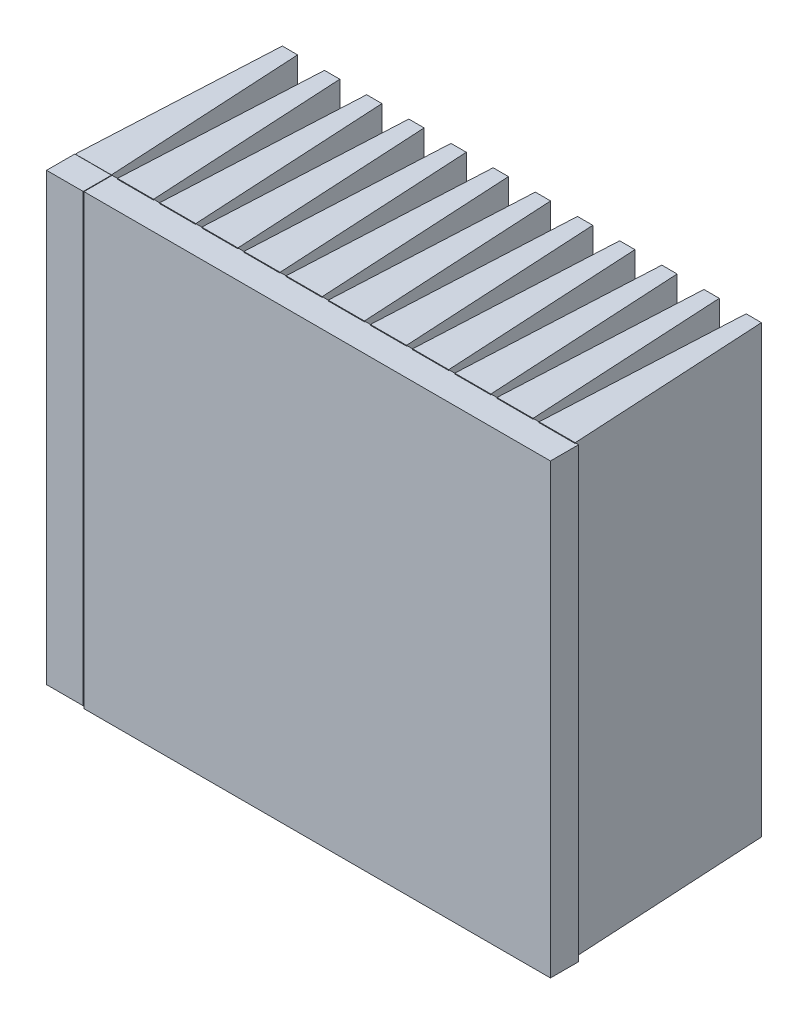
SolidWorks part; units mm, degrees
material "1060 Alloy"
ref_plane "Front Plane" through (0, 0, 0) normal (0, 0, 1) x (1, 0, 0)
ref_plane "Top Plane" through (0, 0, 0) normal (0, 1, 0) x (1, 0, 0)
ref_plane "Right Plane" through (0, 0, 0) normal (1, 0, 0) x (0, 0, -1)
sketch "Sketch1" plane through (0, 0, 0) normal (0, 0, 1) x (1, 0, 0)
  line L0 (-91.5934, 78958.1492) -> (-91.5934, -41.8508)
  line L1 (6408.4066, -41.8508) -> (-91.5934, -41.8508)
  line L2 (6408.4066, -41.8508) -> (6408.4066, 78958.1492)
  line L3 (6408.4066, 78958.1492) -> (-91.5934, 78958.1492)
sketch "Sketch2" plane through (0, 0, 0) normal (0, 1, 0) x (1, 0, 0)
  line L0 (0, 0) -> (1767.7351, 34955.3302)
  line L1 (6408.4066, 0) -> (4484.4459, 34947.0796)
  line L2 (6408.4066, 0) -> (-91.5934, 0) construction
  line L3 (1767.7351, 34955.3302) -> (4484.4459, 34947.0796)
  line L4 (7478.0557, 0) -> (9245.7908, 34955.3302)
  line L5 (13886.4623, 0) -> (11962.5016, 34947.0796)
  line L6 (9245.7908, 34955.3302) -> (11962.5016, 34947.0796)
  line L7 (14956.1114, 0) -> (16723.8465, 34955.3302)
  line L8 (21364.518, 0) -> (19440.5573, 34947.0796)
  line L9 (16723.8465, 34955.3302) -> (19440.5573, 34947.0796)
  line L10 (22434.1671, 0) -> (24201.9022, 34955.3302)
  line L11 (28842.5737, 0) -> (26918.613, 34947.0796)
  line L12 (24201.9022, 34955.3302) -> (26918.613, 34947.0796)
  line L13 (29912.2228, 0) -> (31679.9579, 34955.3302)
  line L14 (36320.6294, 0) -> (34396.6687, 34947.0796)
  line L15 (31679.9579, 34955.3302) -> (34396.6687, 34947.0796)
  line L16 (37390.2785, 0) -> (39158.0136, 34955.3302)
  line L17 (43798.6851, 0) -> (41874.7244, 34947.0796)
  line L18 (39158.0136, 34955.3302) -> (41874.7244, 34947.0796)
  line L19 (44868.3342, 0) -> (46636.0693, 34955.3302)
  line L20 (51276.7408, 0) -> (49352.7801, 34947.0796)
  line L21 (46636.0693, 34955.3302) -> (49352.7801, 34947.0796)
  line L22 (52346.3898, 0) -> (54114.1249, 34955.3302)
  line L23 (58754.7965, 0) -> (56830.8357, 34947.0796)
  line L24 (54114.1249, 34955.3302) -> (56830.8357, 34947.0796)
  line L25 (59824.4455, 0) -> (61592.1806, 34955.3302)
  line L26 (66232.8521, 0) -> (64308.8914, 34947.0796)
  line L27 (61592.1806, 34955.3302) -> (64308.8914, 34947.0796)
  line L28 (67302.5012, 0) -> (69070.2363, 34955.3302)
  line L29 (73710.9078, 0) -> (71786.9471, 34947.0796)
  line L30 (69070.2363, 34955.3302) -> (71786.9471, 34947.0796)
  line L31 (74780.5569, 0) -> (76548.292, 34955.3302)
  line L32 (81188.9635, 0) -> (79265.0028, 34947.0796)
  line L33 (76548.292, 34955.3302) -> (79265.0028, 34947.0796)
  line L34 (82258.6126, 0) -> (84026.3477, 34955.3302)
  line L35 (88667.0192, 0) -> (86743.0585, 34947.0796)
  line L36 (84026.3477, 34955.3302) -> (86743.0585, 34947.0796)
  line L37 (7478.0557, 0) -> (13886.4623, 0)
  line L38 (14956.1114, 0) -> (21364.518, 0)
  line L39 (22434.1671, 0) -> (28842.5737, 0)
  line L40 (29912.2228, 0) -> (36320.6294, 0)
  line L41 (37390.2785, 0) -> (43798.6851, 0)
  line L42 (44868.3342, 0) -> (51276.7408, 0)
  line L43 (52346.3898, 0) -> (58754.7965, 0)
  line L44 (59824.4455, 0) -> (66232.8521, 0)
  line L45 (68289.4582, 516.4602) -> (67302.5012, 0)
  line L46 (67302.5012, 0) -> (73710.9078, 0)
  line L47 (74780.5569, 0) -> (81188.9635, 0)
  line L48 (82258.6126, 0) -> (88667.0192, 0)
  line L49 (0, 0) -> (88667.0192, 0)
  line L50 (88667.0192, -5000) -> (0, -5000)
  line L51 (0, -5000) -> (0, 0)
  line L52 (88667.0192, -5000) -> (88667.0192, 0)
  line L53 (0, 0) -> (6408.4066, 0)
  line L54 (88667.0192, -5000) -> (88667.0192, 0)
  line L55 (88667.0192, 0) -> (0, 0)
  line L56 (0, -5000) -> (88667.0192, -5000)
  line L57 (0, 0) -> (88667.0192, 0)
  line L58 (88667.0192, -5000) -> (0, -5000)
  line L60 (0, 0) -> (88667.0192, 0)
  line L61 (0, 0) -> (0, -5000)
  line L62 (0, -5000) -> (88667.0192, -5000)
  line L63 (88667.0192, 0) -> (88667.0192, -5000)
  line L64 (0, 0) -> (88667.0192, 0)
  line L65 (0, 0) -> (0, -5000)
  line L66 (0, -5000) -> (88667.0192, -5000)
  line L67 (88667.0192, 0) -> (88667.0192, -5000)
  point P54 (0, 0)
  dimension "D1" = 12
extrude "Boss-Extrude2" add sketch "Sketch2" along normal blind 79000 contours L53 L1 L3 L0 | L37 L5 L6 L4 | L38 L8 L9 L7 | L39 L11 L12 L10 | L40 L14 L15 L13 | L41 L17 L18 L16 | L42 L20 L21 L19 | L43 L23 L24 L22 | L44 L26 L27 L25 | L46 L29 L30 L28 | L47 L32 L33 L31 | L48 L35 L36 L34
extrude "Boss-Extrude3" add sketch "Sketch1" along normal blind 5000 contours L0 L1 L2 L3
ref_plane "Plane1" through (6408.4066, -41.8508, 5000) normal (0, 1, 0) x (1, 0, 0)
ref_plane "Plane2" through (6408.4066, -41.8508, 0) normal (0, 0, -1) x (-1, 0, 0)
sketch "Sketch5" plane through (6408.4066, 864.4696, -1423.2541) normal (1, 0, 0) x (0, 0, -1)
  line L1 (-1290.2711, -1412.6424) -> (-6290.2711, -1412.6424)
  line L2 (-1290.2711, -1412.6424) -> (-1290.2711, 77999.0673)
  line L3 (-1290.2711, 77999.0673) -> (-6290.2711, 77999.0673)
  line L4 (-6290.2711, -1412.6424) -> (-6290.2711, 77999.0673)
extrude "Boss-Extrude4" add sketch "Sketch5" along normal blind 82730
